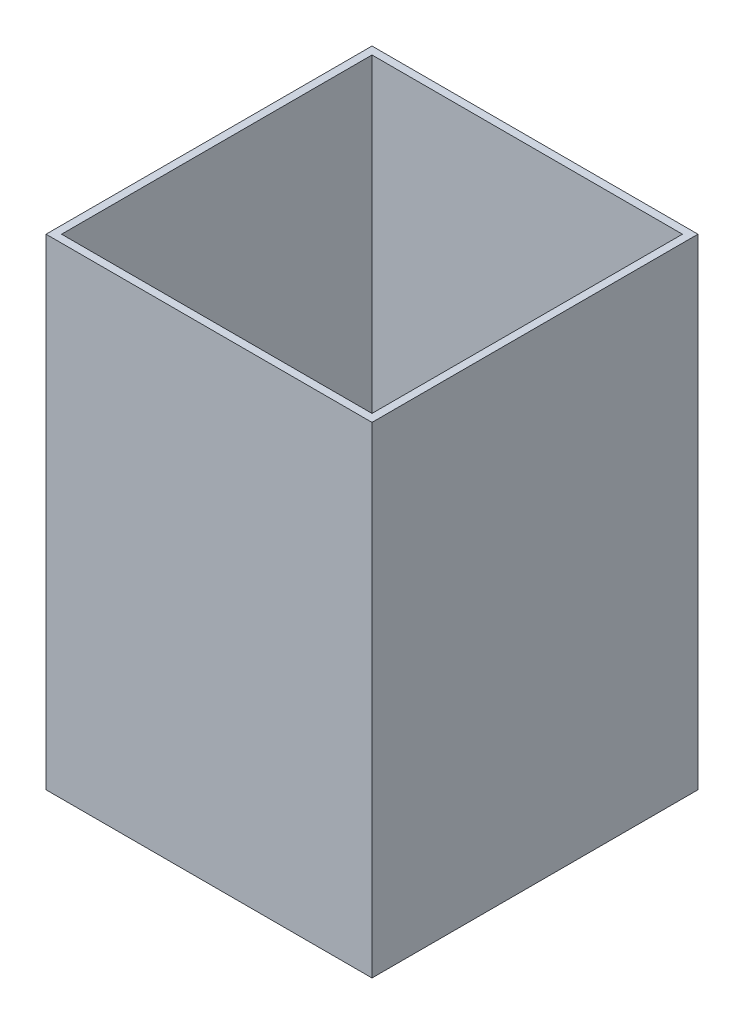
SolidWorks part; units mm, degrees
material "有机玻璃 (TM) GS 丙烯酸铸钣"
ref_plane "前视基准面" through (0, 0, 0) normal (0, 0, 1) x (1, 0, 0)
ref_plane "上视基准面" through (0, 0, 0) normal (0, 1, 0) x (1, 0, 0)
ref_plane "右视基准面" through (0, 0, 0) normal (1, 0, 0) x (0, 0, -1)
other "Configuration Table"
sketch "草图1" plane through (0, 0, 0) normal (0, 1, 0) x (1, 0, 0)
  line L1 (-105, 105) -> (105, 105)
  line L2 (-105, 105) -> (-105, -105)
  line L3 (-105, -105) -> (105, -105)
  line L4 (105, 105) -> (105, -105)
  line L5 (-105, 105) -> (105, -105) construction
  line L6 (-105, -105) -> (105, 105) construction
  point P0 (0, 0)
  dimension "D1" = 210
  dimension "D2" = 210
extrude "凸台-拉伸1" add sketch "草图1" along normal blind 310
sketch "草图2" plane through (0, 0, 0) normal (0, 1, 0) x (1, 0, 0)
  line L1 (-100, 100) -> (100, 100)
  line L2 (-100, 100) -> (-100, -100)
  line L3 (-100, -100) -> (100, -100)
  line L4 (100, 100) -> (100, -100)
  line L5 (-100, 100) -> (100, -100) construction
  line L6 (-100, -100) -> (100, 100) construction
  point P0 (0, 0)
  dimension "D1" = 200
  dimension "D2" = 200
extrude "切除-拉伸1" cut sketch "草图2" against normal offset from surface (300 mm away) 10 from surface at 310 up to face at (0, 0, 0) starting at face at (0, 310, 0)
